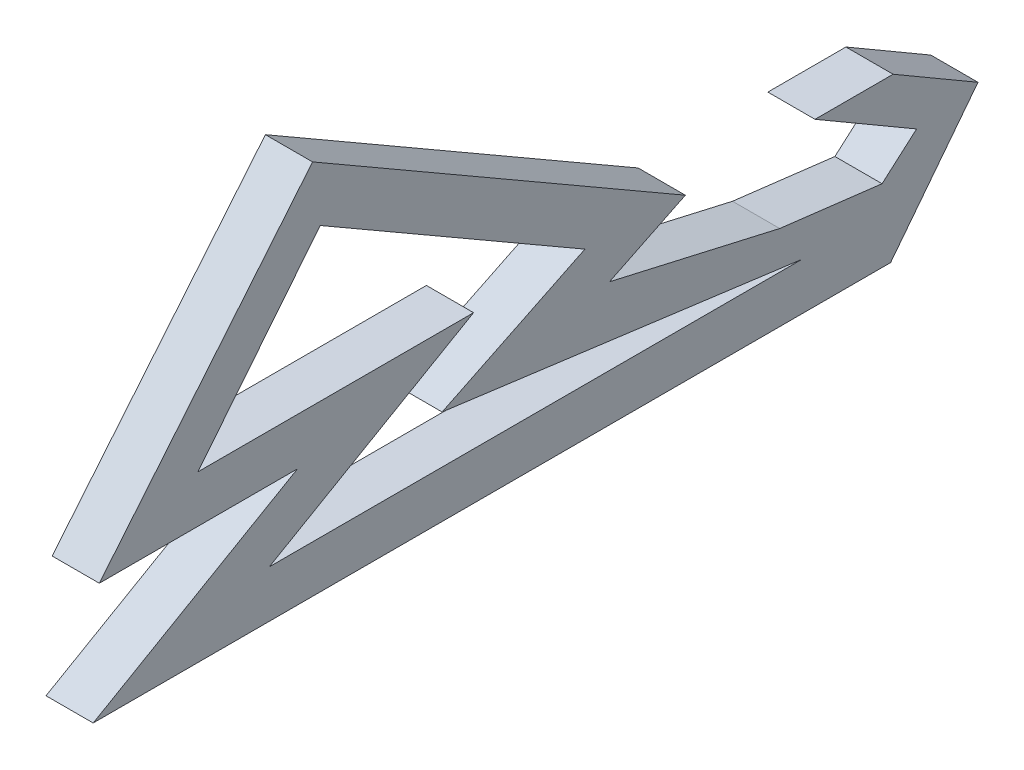
SolidWorks part; units mm, degrees
ref_plane "Front Plane" through (0, 0, 0) normal (0, 0, 1) x (1, 0, 0)
ref_plane "Top Plane" through (0, 0, 0) normal (0, 1, 0) x (1, 0, 0)
ref_plane "Right Plane" through (0, 0, 0) normal (1, 0, 0) x (0, 0, -1)
sketch "Sketch1" plane through (0, 0, 0) normal (1, 0, 0) x (0, 0, -1)
  line L0 (-84.5, 0) -> (84.5, 0)
  line L1 (-84.5, 0) -> (-41.1987, 25)
  line L2 (-41.1987, 25) -> (-83.1987, 25)
  line L4 (-38.0059, 79.737) -> (41.0019, 34.1218)
  line L5 (41.0019, 34.1218) -> (24.9115, 26.2739)
  line L11 (103.0227, 23.8373) -> (84.5, 0)
  line L12 (-27.3145, 0) -> (-27.3145, 10) construction
  line L13 (-38.0858, 26.7972) -> (-33.0858, 18.137) construction
  line L14 (-47.1795, 10) -> (-7.4494, 10)
  line L15 (-33.0966, 25) -> (-33.0966, 35) construction
  line L16 (-52.7705, 61.8543) -> (-45.0591, 55.4876) construction
  line L17 (-12.4421, 64.9777) -> (-17.4421, 56.3174) construction
  line L18 (8.968, 18.4978) -> (4.5842, 27.4857) construction
  line L19 (12.1404, 24.7561) -> (9.7212, 15.0531) construction
  line L20 (-7.4494, 10) -> (29.9883, 10)
  line L21 (-47.1795, 10) -> (-18.9922, 26.2739)
  line L22 (-3.8782, 35) -> (-62.315, 35)
  line L23 (-18.9922, 26.2739) -> (-3.8782, 35)
  line L24 (-10.5458, 20.1063) -> (19.7143, 34.8652)
  line L27 (1.5034, 45.3792) -> (-36.3876, 67.2556)
  line L28 (1.5034, 45.3792) -> (19.7143, 34.8652)
  line L29 (85.0303, 34.3106) -> (103.0227, 23.8373)
  line L30 (85.0303, 34.3106) -> (68.4811, 34.3106)
  line L31 (68.4811, 34.3106) -> (90.0065, 21.7808)
  line L32 (90.0065, 21.7808) -> (82.6905, 15.3854)
  line L33 (-83.1987, 25) -> (-38.0059, 79.737)
  line L34 (60.9997, 18.0147) -> (82.6905, 15.3854)
  line L35 (-36.3876, 67.2556) -> (-62.315, 35)
  line L36 (-10.5458, 20.1063) -> (65.7565, 10)
  line L37 (65.7565, 10) -> (29.9883, 10)
  line L38 (60.9997, 18.0147) -> (24.9115, 26.2739)
  point P4 (0, 0)
  point P21 (-27.3145, 10)
  point P34 (-33.0966, 35)
  point P37 (-33.0858, 18.137)
  point P39 (-33.0966, 35)
  point P41 (-55.2083, 53.4808)
  point P43 (-17.4421, 56.3174)
  point P44 (-58.5038, 47.7729)
  point P45 (4.5842, 27.4857)
  point P47 (-45.0591, 55.4876)
  point P48 (-45.0591, 55.4876)
  point P49 (9.7212, 15.0531)
  point P50 (-17.4421, 56.3174)
  dimension "D1" = 169
  dimension "D2" = 50
  dimension "D3" = 30
  dimension "D4" = 42
  dimension "D5" = 10
  dimension "D6" = 90
  dimension "D10" = 56
  dimension "D18" = 10
  dimension "D20" = 10
  dimension "D21" = 10
  dimension "D22" = 10
  dimension "D24" = 10
  dimension "D25" = 10
  dimension "D27" = 90
extrude "Boss-Extrude1" add sketch "Sketch1" along normal blind 10
